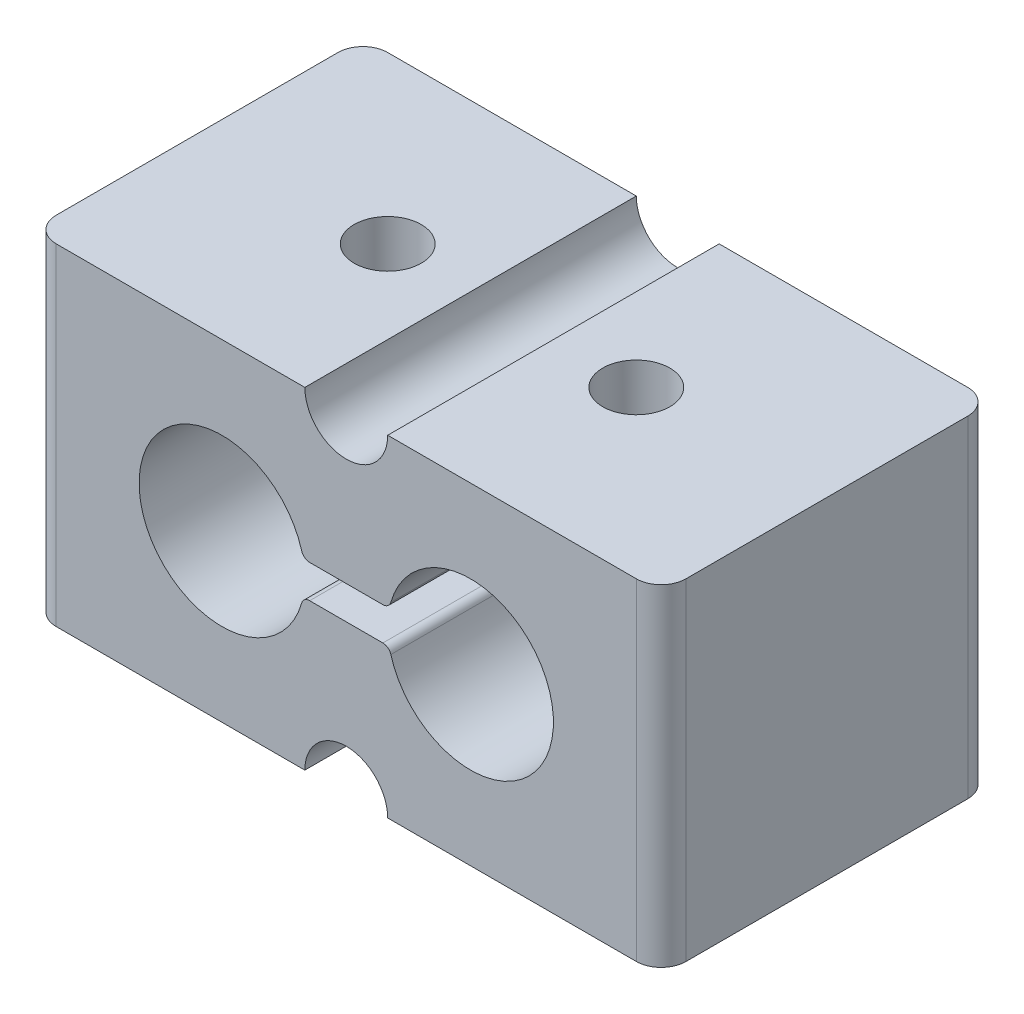
SolidWorks part; units mm, degrees
ref_plane "前视基准面" through (0, 0, 0) normal (0, 0, 1) x (1, 0, 0)
ref_plane "上视基准面" through (0, 0, 0) normal (0, 1, 0) x (1, 0, 0)
ref_plane "右视基准面" through (0, 0, 0) normal (1, 0, 0) x (0, 0, -1)
sketch "草图1" plane through (0, 0, 0) normal (0, 0, 1) x (1, 0, 0)
  line L0 (7.5, 0) -> (-7.5, 0) construction
  line L1 (2.601, 1) -> (-2.601, 1)
  line L2 (19, -10) -> (-19, -10)
  line L3 (19, -10) -> (19, 10)
  line L4 (19, 10) -> (-19, 10)
  line L5 (-19, -10) -> (-19, 10)
  line L6 (19, -10) -> (-19, 10) construction
  line L7 (19, 10) -> (-19, -10) construction
  line L8 (2.601, -1) -> (-2.601, -1)
  arc A0 (-2.601, 1) -> (-2.601, -1) centre (-7.5, 0) ccw
  arc A1 (2.601, -1) -> (2.601, 1) centre (7.5, 0) ccw
  point P4 (0, 0)
  point P8 (0, 0)
  dimension "D1" = 10
  dimension "D2" = 15
  dimension "D3" = 20
  dimension "D4" = 38
  dimension "D5" = 1
extrude "凸台-拉伸1" add sketch "草图1" along normal mid plane 20
sketch "草图2" plane through (0, 10, 0) normal (0, 1, 0) x (1, 0, 0)
  line L0 (7.5, 0) -> (-7.5, 0) construction
  circle A2 centre (-7.5, 0) radius 2.025
  circle A3 centre (7.5, 0) radius 2.025
  point P3 (0, 0)
  dimension "D1" = 15
  dimension "D2" = 4.05
extrude "切除-拉伸1" cut sketch "草图2" against normal through all
fillet "圆角1" radius 0.5 4 edges at (2.601, 1, 0) (-2.601, 1, 0) (-2.601, -1, 0) (2.601, -1, 0)
sketch "草图3" plane through (0, 0, 10) normal (0, 0, 1) x (1, 0, 0)
  line L0 (19, 10) -> (-19, 10) construction
  line L1 (-19, -10) -> (19, -10) construction
  circle A0 centre (0, 10) radius 2.5
  circle A1 centre (0, -10) radius 2.5
  dimension "D1" = 5
extrude "切除-拉伸2" cut sketch "草图3" against normal through all
fillet "圆角2" radius 1.5 4 edges at (-19, 0, -10) (19, 0, -10) (19, 0, 10) (-19, 0, 10)
